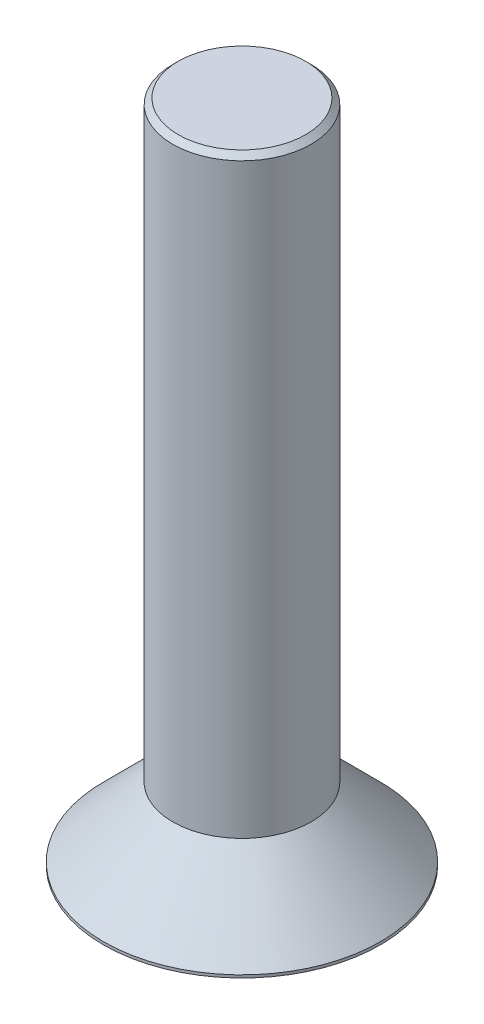
SolidWorks part; units mm, degrees
ref_plane "前视基准面" through (0, 0, 0) normal (0, 0, 1) x (1, 0, 0)
ref_plane "上视基准面" through (0, 0, 0) normal (0, 1, 0) x (1, 0, 0)
ref_plane "右视基准面" through (0, 0, 0) normal (1, 0, 0) x (0, 0, -1)
sketch "草图1" plane through (0, 0, 0) normal (0, 1, 0) x (1, 0, 0)
  circle A0 centre (0, 0) radius 5
  dimension "D1" = 10
extrude "凸台-拉伸1" add sketch "草图1" along normal blind 2.6
chamfer "倒角1" distance 2.5 angle 45 1 edges at (0, 2.6, 5)
sketch "草图2" plane through (0, 0, 0) normal (0, -1, 0) x (1, 0, 0)
  line L1 (1.54, -0.8891) -> (1.54, 0.8891)
  line L2 (1.54, 0.8891) -> (0, 1.7782)
  line L3 (0, 1.7782) -> (-1.54, 0.8891)
  line L4 (-1.54, 0.8891) -> (-1.54, -0.8891)
  line L5 (-1.54, -0.8891) -> (0, -1.7782)
  line L6 (0, -1.7782) -> (1.54, -0.8891)
  circle A0 centre (0, 0) radius 1.54 construction
  dimension "D1" = 3.08
extrude "切除-拉伸1" cut sketch "草图2" against normal blind 0.95
sketch "草图3" plane through (0, 2.6, 0) normal (0, 1, 0) x (1, 0, 0)
  circle A0 centre (0, 0) radius 2.5
  dimension "D1" = 5
extrude "凸台-拉伸2" add sketch "草图3" along normal blind 21.4
chamfer "倒角2" distance 0.2 angle 45 1 edges at (0, 24, 2.5)
